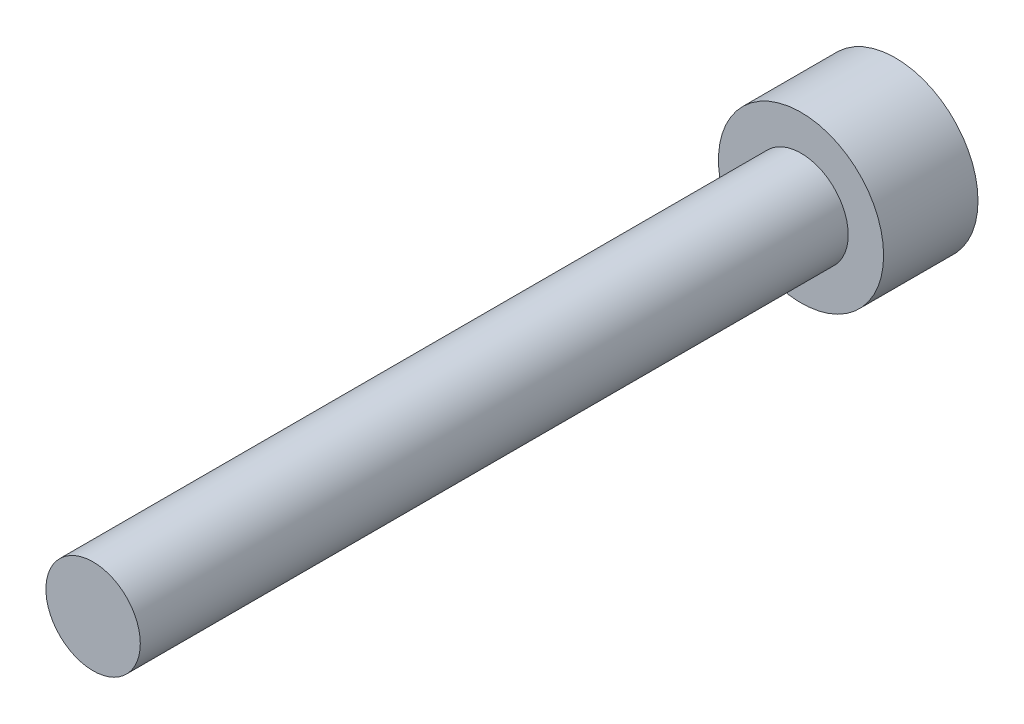
SolidWorks part; units mm, degrees
material "Acero aleado"
ref_plane "Alzado" through (0, 0, 0) normal (0, 0, 1) x (1, 0, 0)
ref_plane "Planta" through (0, 0, 0) normal (0, 1, 0) x (1, 0, 0)
ref_plane "Vista lateral" through (0, 0, 0) normal (1, 0, 0) x (0, 0, -1)
sketch "Croquis1" plane through (0, 0, 0) normal (0, 0, 1) x (1, 0, 0)
  circle A0 centre (0, 0) radius 3.5
  dimension "D1" = 7
extrude "Cabeza" add sketch "Croquis1" along normal blind 4 from offset 4
sketch "Croquis2" plane through (0, 0, 0) normal (0, 0, 1) x (1, 0, 0)
  circle A0 centre (0, 0) radius 2
  dimension "D1" = 4
extrude "Cuerpo" add sketch "Croquis2" along normal blind 30
sketch "Croquis3" plane through (0, 0, 0) normal (0, 0, 1) x (1, 0, 0)
  line L0 (1.7321, 0) -> (0.866, 1.5)
  line L1 (0.866, 1.5) -> (-0.866, 1.5)
  line L2 (-0.866, 1.5) -> (-1.7321, 0)
  line L3 (-1.7321, 0) -> (-0.866, -1.5)
  line L4 (-0.866, -1.5) -> (0.866, -1.5)
  line L5 (0.866, -1.5) -> (1.7321, 0)
  dimension "D1" = 1.7321
  dimension "D2" = 0.866
  dimension "D3" = 1.5
  dimension "D4" = 0.866
  dimension "D5" = 1.5
  dimension "D6" = 1.7321
  dimension "D7" = 0.866
  dimension "D8" = 1.5
  dimension "D9" = 0.866
  dimension "D10" = 1.5
extrude "Hexagono_interior" cut sketch "Croquis3" along normal blind 2 from offset 4
